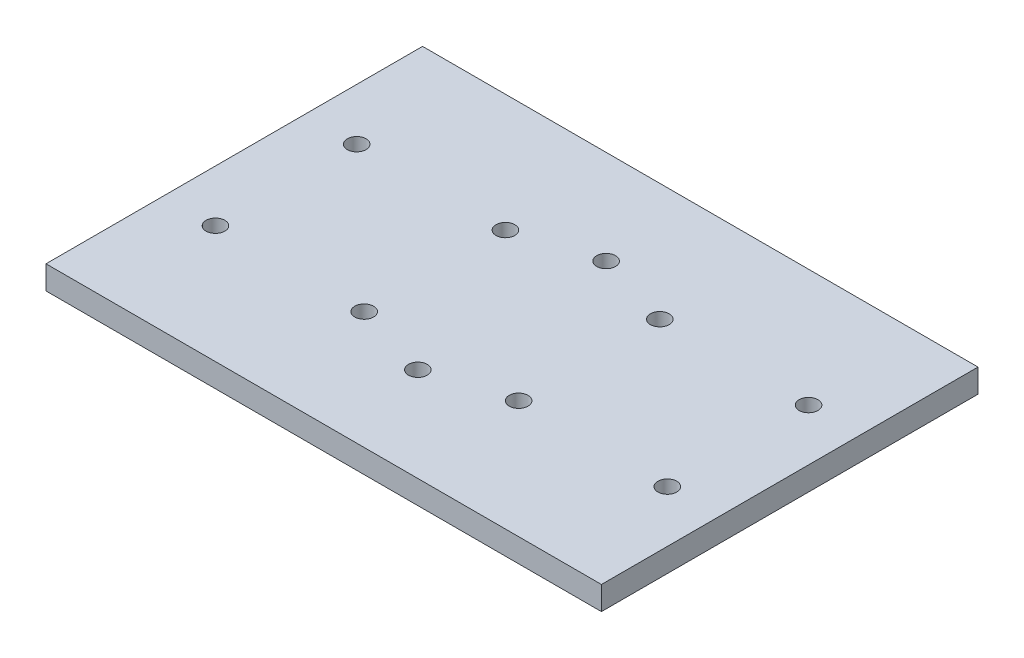
SolidWorks part; units mm, degrees
ref_plane "Front Plane" through (0, 0, 0) normal (0, 0, 1) x (1, 0, 0)
ref_plane "Top Plane" through (0, 0, 0) normal (0, 1, 0) x (1, 0, 0)
ref_plane "Right Plane" through (0, 0, 0) normal (1, 0, 0) x (0, 0, -1)
sketch "Sketch1" plane through (0, 0, 0) normal (0, 1, 0) x (1, 0, 0)
  line L1 (-300.0571, 77.9643) -> (-182.0571, 77.9643)
  line L2 (-300.0571, 77.9643) -> (-300.0571, -2.0357)
  line L3 (-300.0571, -2.0357) -> (-182.0571, -2.0357)
  line L4 (-182.0571, 77.9643) -> (-182.0571, -2.0357)
  dimension "D1" = 118
  dimension "D2" = 80
extrude "Boss-Extrude1" add sketch "Sketch1" along normal blind 5
sketch "Sketch2" plane through (0, 5, 0) normal (0, 1, 0) x (1, 0, 0)
  line L0 (-241.0571, 77.9643) -> (-241.0571, -2.0357) construction
  line L1 (-182.0571, 77.9643) -> (-300.0571, 77.9643) construction
  line L2 (-300.0571, -2.0357) -> (-182.0571, -2.0357) construction
  line L3 (-241.0571, -2.0357) -> (-241.0571, 37.9643) construction
  line L4 (-241.0571, 37.9643) -> (-300.0571, 37.9643) construction
  line L5 (-300.0571, 77.9643) -> (-300.0571, -2.0357) construction
  circle A0 centre (-289.0571, 52.9643) radius 2
  circle A1 centre (-257.4571, 52.9643) radius 2
  circle A2 centre (-224.6571, 52.9643) radius 2
  circle A3 centre (-193.0571, 52.9643) radius 2
  circle A4 centre (-193.0571, 22.9643) radius 2
  circle A5 centre (-224.6571, 22.9643) radius 2
  circle A6 centre (-257.4571, 22.9643) radius 2
  circle A7 centre (-289.0571, 22.9643) radius 2
  circle A8 centre (-241.0571, 57.9643) radius 2
  circle A9 centre (-241.0571, 17.9643) radius 2
  dimension "D1" = 48
  dimension "D3" = 4
  dimension "D4" = 4
  dimension "D7" = 4
  dimension "D2" = 16.4
  dimension "D5" = 15
  dimension "D6" = 15
  dimension "D8" = 20
extrude "Cut-Extrude1" cut sketch "Sketch2" against normal blind 5
